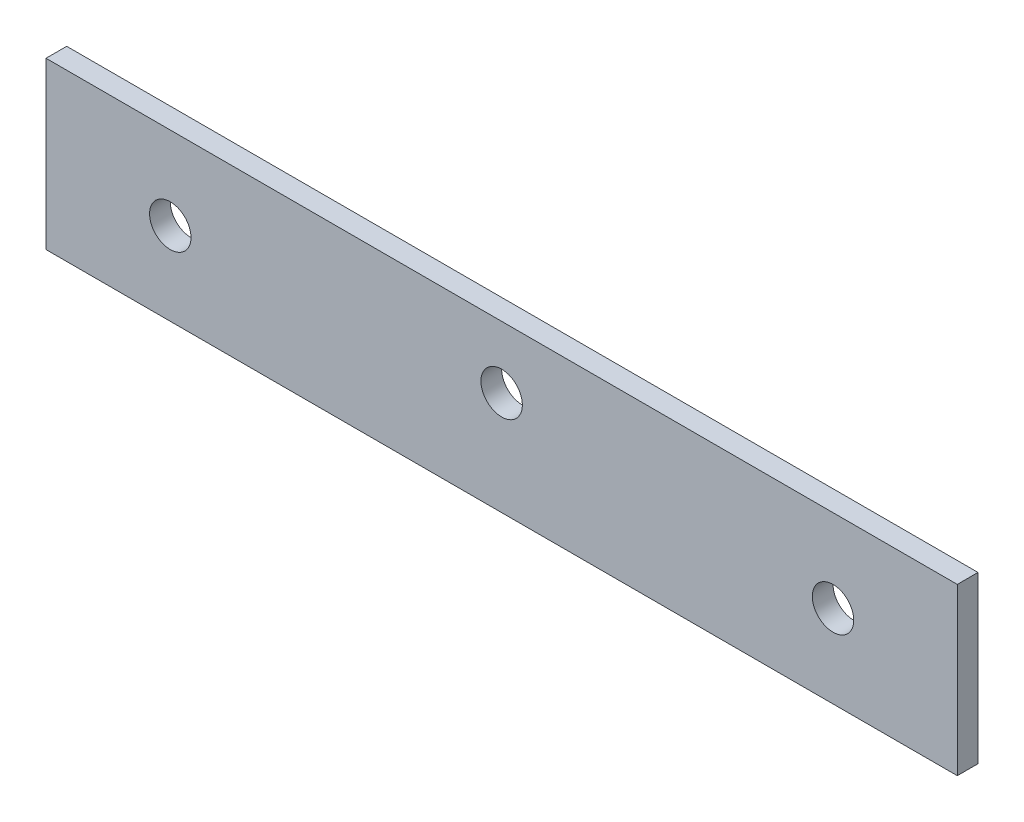
SolidWorks part; units mm, degrees
material "5052-H34"
ref_plane "正面" through (0, 0, 0) normal (0, 0, 1) x (1, 0, 0)
ref_plane "平面" through (0, 0, 0) normal (0, 1, 0) x (1, 0, 0)
ref_plane "右側面" through (0, 0, 0) normal (1, 0, 0) x (0, 0, -1)
sketch "ｽｹｯﾁ1" plane through (0, 0, 0) normal (0, 0, 1) x (1, 0, 0)
  line L0 (110, 0) -> (-110, 0) construction
  line L1 (-110, 20) -> (110, 20)
  line L2 (-110, 20) -> (-110, -20)
  line L3 (-110, -20) -> (110, -20)
  line L4 (110, 20) -> (110, -20)
  line L5 (-110, 20) -> (110, -20) construction
  line L6 (-110, -20) -> (110, 20) construction
  line L7 (0, -20) -> (0, 20) construction
  circle A0 centre (80, 0) radius 5
  circle A1 centre (-80, 0) radius 5
  circle A2 centre (0, 5) radius 5
  point P0 (0, 0)
  dimension "D3" = 10
  dimension "D4" = 80
  dimension "D6" = 5
  dimension "D1" = 40
  dimension "D2" = 220
  dimension "D5" = 80
extrude "ﾎﾞｽ - 押し出し1" add sketch "ｽｹｯﾁ1" along normal blind 5
